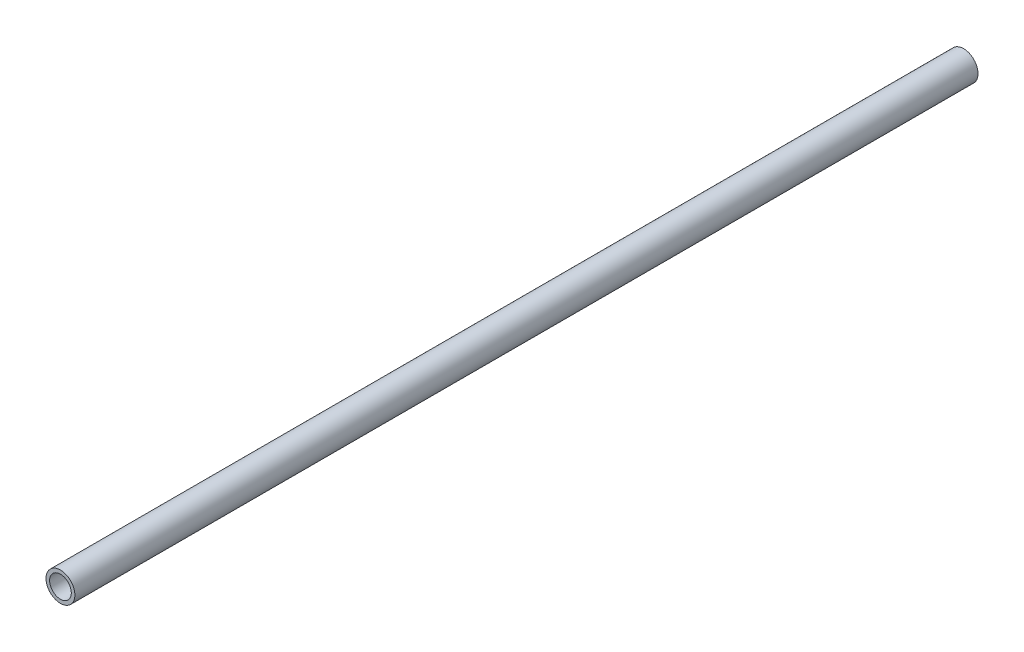
SolidWorks part; units mm, degrees
ref_plane "Front Plane" through (0, 0, 0) normal (0, 0, 1) x (1, 0, 0)
ref_plane "Top Plane" through (0, 0, 0) normal (0, 1, 0) x (1, 0, 0)
ref_plane "Right Plane" through (0, 0, 0) normal (1, 0, 0) x (0, 0, -1)
sketch "Sketch1" plane through (0, 0, 0) normal (0, 0, 1) x (1, 0, 0)
  circle A0 centre (0, 0) radius 12.7
  dimension "D1" = 25.4
extrude "Boss-Extrude1" add sketch "Sketch1" along normal blind 793.75
shell "Shell1" thickness 3.175
